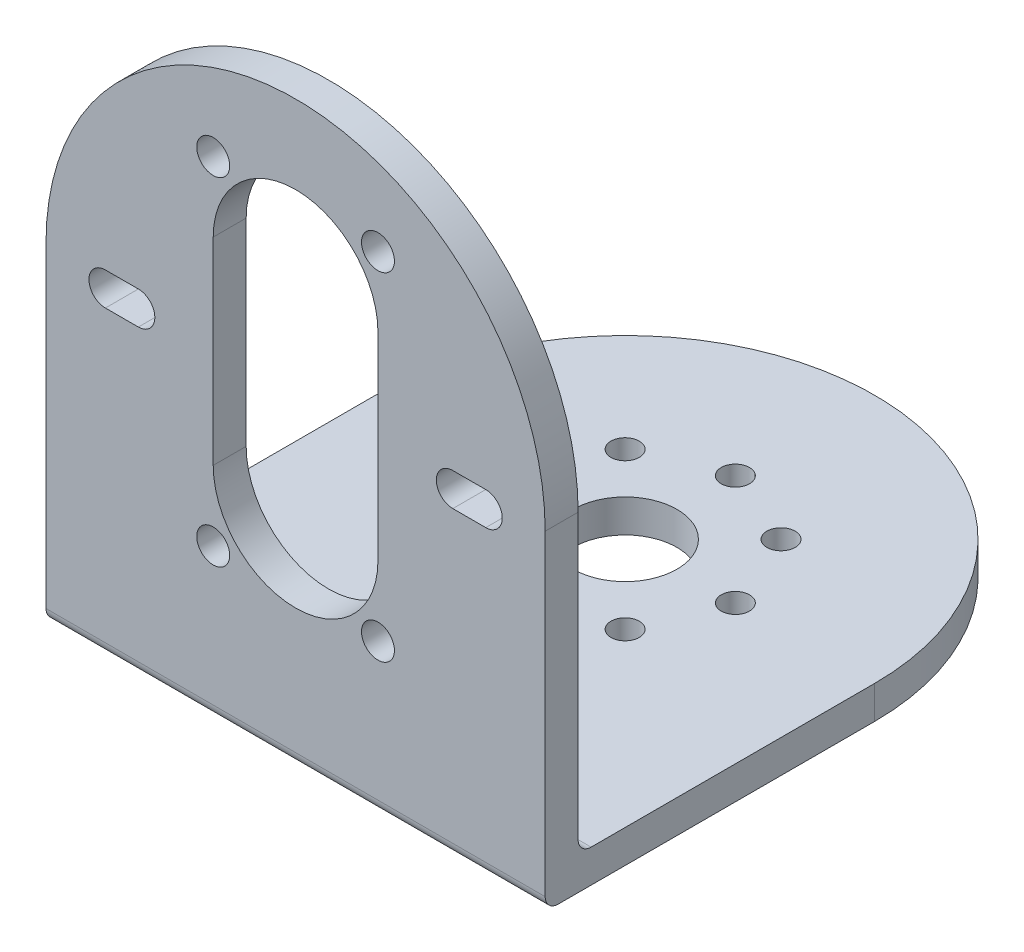
SolidWorks part; units mm, degrees
material "1060 Alloy"
ref_plane "Front" through (0, 0, 0) normal (0, 0, 1) x (1, 0, 0)
ref_plane "Top" through (0, 0, 0) normal (0, 1, 0) x (1, 0, 0)
ref_plane "Right" through (0, 0, 0) normal (1, 0, 0) x (0, 0, -1)
sketch "Sketch1" plane through (0, 0, 0) normal (0, 1, 0) x (1, 0, 0)
  line L0 (-19.24, 0) -> (-19.24, -25.4)
  line L1 (19.24, 0) -> (19.24, -25.4)
  line L2 (19.24, -25.4) -> (-19.24, -25.4)
  arc A0 (19.24, 0) -> (-19.24, 0) centre (0, 0) ccw
  circle A1 centre (0, 0) radius 4
  dimension "D1" = 38.48
  dimension "D2" = 8
  dimension "D3" = 25.4
extrude "Boss-Extrude1" add sketch "Sketch1" along normal blind 2.54
ref_plane "Plane1" through (0, 2.54, 0) normal (0, 1, 0) x (1, 0, 0)
sketch "Sketch2" plane through (0, 2.54, 0) normal (0, 1, 0) x (1, 0, 0)
  line L0 (-19.24, -25.4) -> (19.24, -25.4) construction
  circle A0 centre (0, 8.5) radius 1.09
  circle A1 centre (0, 0) radius 4 construction
  dimension "D1" = 2.18
  dimension "D2" = 8.5
  dimension "D3" = 33.9
extrude "Cut-Extrude1" cut sketch "Sketch2" against normal mid plane 10
pattern_circular "CirPattern1" count 8 over 360 about axis through (0, 0, 0) along (0, 1, 0) of "Cut-Extrude1"
ref_plane "Plane2" through (0, 0, 25.4) normal (0, 0, 1) x (1, 0, 0)
sketch "Sketch3" plane through (0, 0, 25.4) normal (0, 0, 1) x (1, 0, 0)
  line L0 (19.24, 2.54) -> (19.24, 25.4)
  line L1 (21.164, 2.54) -> (-21.164, 2.54) construction
  line L2 (19.24, 2.54) -> (19.24, 0) construction
  line L3 (-19.24, 2.54) -> (-19.24, 25.4)
  line L4 (0, 44.64) -> (0, 0) construction
  line L5 (6.35, 32.24) -> (6.35, 17)
  line L6 (-6.35, 32.24) -> (-6.35, 17)
  line L7 (6.35, 37.62) -> (6.35, 11.62) construction
  line L8 (6.35, 24.62) -> (-6.35, 24.62) construction
  line L9 (14.66, 25.89) -> (12.12, 25.89)
  line L10 (14.66, 23.35) -> (12.12, 23.35)
  line L11 (-14.66, 23.35) -> (-12.12, 23.35)
  line L12 (-14.66, 25.89) -> (-12.12, 25.89)
  line L13 (19.24, 2.54) -> (-19.24, 2.54)
  arc A0 (19.24, 25.4) -> (-19.24, 25.4) centre (0, 25.4) ccw
  arc A1 (6.35, 32.24) -> (-6.35, 32.24) centre (0, 32.24) ccw
  arc A2 (6.35, 17) -> (-6.35, 17) centre (0, 17) cw
  circle A3 centre (6.35, 37.62) radius 1.27
  circle A4 centre (6.35, 11.62) radius 1.27
  circle A5 centre (-6.35, 11.62) radius 1.27
  circle A6 centre (-6.35, 37.62) radius 1.27
  arc A7 (12.12, 25.89) -> (12.12, 23.35) centre (12.12, 24.62) ccw
  arc A8 (14.66, 25.89) -> (14.66, 23.35) centre (14.66, 24.62) cw
  arc A9 (-14.66, 25.89) -> (-14.66, 23.35) centre (-14.66, 24.62) ccw
  arc A10 (-12.12, 25.89) -> (-12.12, 23.35) centre (-12.12, 24.62) cw
  point P25 (6.35, 24.62)
  point P36 (10.85, 24.62)
  point P43 (-10.85, 24.62)
  dimension "D5" = 2.54
  dimension "D1" = 22.86
  dimension "D2" = 15.24
  dimension "D3" = 12.7
  dimension "D4" = 17
  dimension "D6" = 26
  dimension "D7" = 2.54
  dimension "D8" = 2.54
  dimension "D9" = 4.5
extrude "Boss-Extrude2" add sketch "Sketch3" against normal blind 2.54
fillet "Fillet1" radius 1 2 edges at (0, 0, 25.4)
